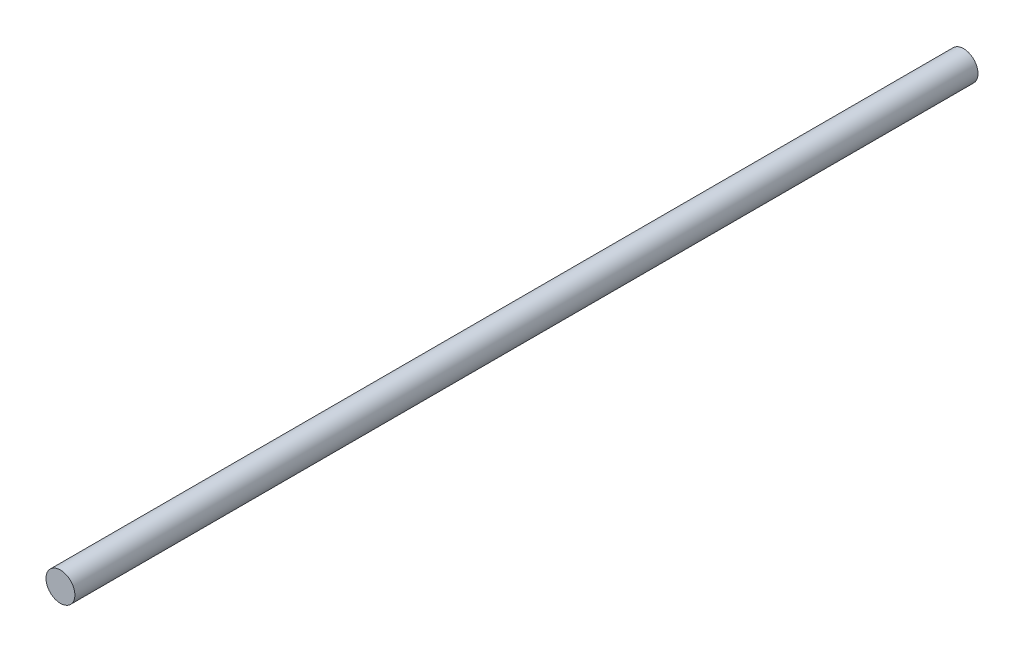
SolidWorks part; units mm, degrees
ref_plane "Front" through (0, 0, 0) normal (0, 0, 1) x (1, 0, 0)
ref_plane "Top" through (0, 0, 0) normal (0, 1, 0) x (1, 0, 0)
ref_plane "Right" through (0, 0, 0) normal (1, 0, 0) x (0, 0, -1)
sketch "Эскиз1" plane through (0, 0, 0) normal (0, 0, 1) x (1, 0, 0)
  circle A0 centre (0, 0) radius 4
extrude "Бобышка-Вытянуть1" add sketch "Эскиз1" along normal blind 250
